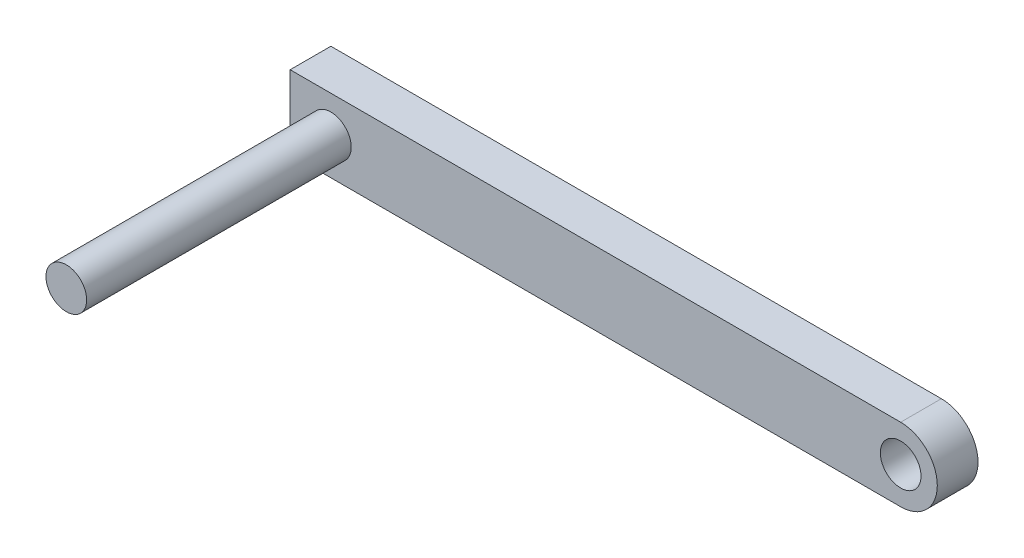
SolidWorks part; units mm, degrees
ref_plane "Plan de face" through (0, 0, 0) normal (0, 0, 1) x (1, 0, 0)
ref_plane "Plan de dessus" through (0, 0, 0) normal (0, 1, 0) x (1, 0, 0)
ref_plane "Plan de droite" through (0, 0, 0) normal (1, 0, 0) x (0, 0, -1)
sketch "Esquisse1" plane through (0, 0, 0) normal (0, 0, 1) x (1, 0, 0)
  line L0 (0, 0) -> (300, 0)
  line L1 (300, 36) -> (0, 36)
  line L2 (0, 36) -> (0, 0)
  arc A0 (300, 0) -> (300, 36) centre (300, 18) ccw
  circle A1 centre (300, 18) radius 10
  dimension "D2" = 20
  dimension "D3" = 300
  dimension "D1" = 36
extrude "Boss.-Extru.1" add sketch "Esquisse1" along normal blind 20
sketch "Esquisse2" plane through (0, 0, 20) normal (0, 0, 1) x (1, 0, 0)
  circle A0 centre (20, 18) radius 10
  circle A1 centre (300, 18) radius 10 construction
  dimension "D1" = 280
  dimension "D2" = 20
extrude "Boss.-Extru.2" add sketch "Esquisse2" along normal blind 130
